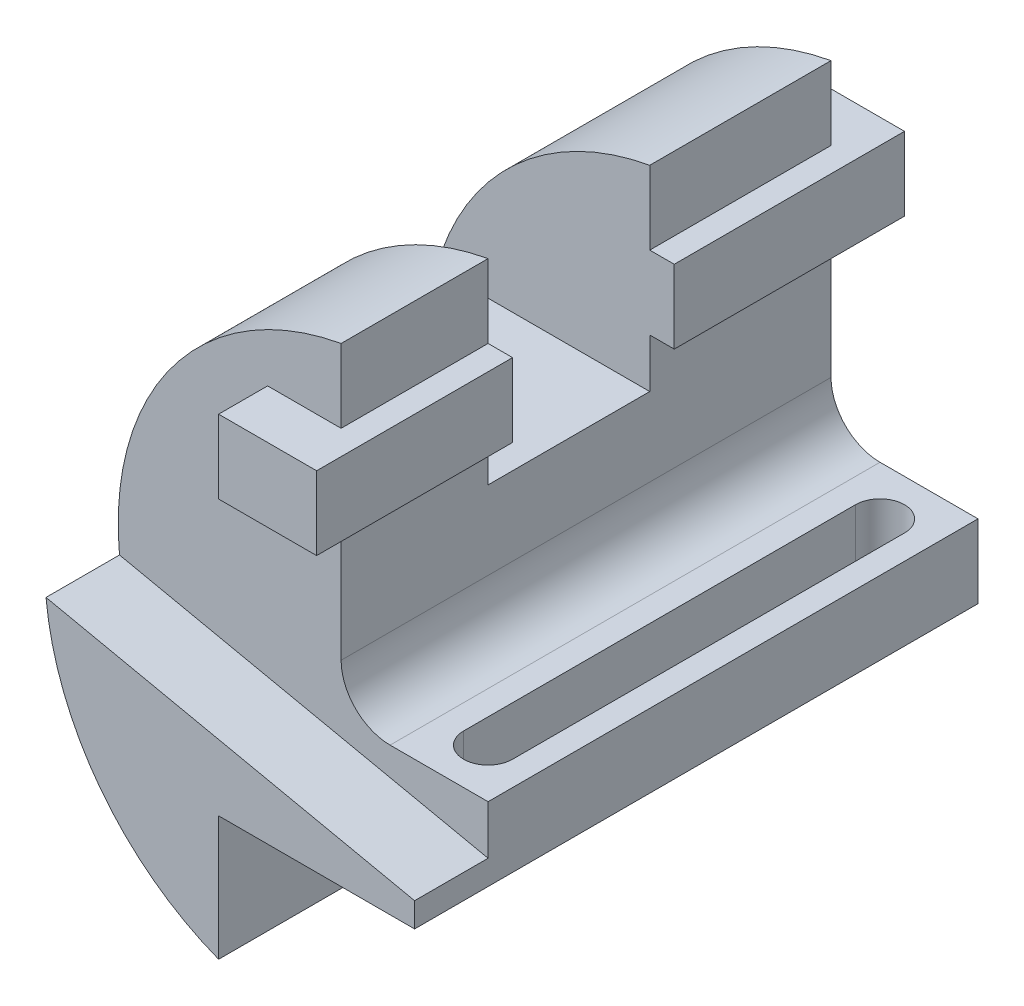
SolidWorks part; units mm, degrees
material "1060 Alloy"
ref_plane "Front Plane" through (0, 0, 0) normal (0, 0, 1) x (1, 0, 0)
ref_plane "Top Plane" through (0, 0, 0) normal (0, 1, 0) x (1, 0, 0)
ref_plane "Right Plane" through (0, 0, 0) normal (1, 0, 0) x (0, 0, -1)
sketch "Sketch1" plane through (0, 0, 0) normal (0, 0, 1) x (1, 0, 0)
  line L0 (0, 0) -> (0, 15)
  line L1 (0, 15) -> (-30, 15)
  line L2 (-30, 15) -> (-30, 81)
  line L3 (0, 0) -> (-40, 0)
  line L4 (-40, 0) -> (-40, -25.3628)
  arc A0 (-30, 81) -> (-40, -25.3628) centre (-20, 26.4083) ccw
  dimension "D5" = 55.5
  dimension "D1" = 15
  dimension "D2" = 20
  dimension "D3" = 40
  dimension "D4" = 10
  dimension "D6" = 66
extrude "Boss-Extrude2" add sketch "Sketch1" along normal blind 115
sketch "Sketch2" plane through (0, 0, 115) normal (0, 0, 1) x (1, 0, 0)
  line L0 (0, 5) -> (-75.235, 20.9917)
  line L1 (0, 0) -> (0, 15) construction
  line L8 (-40, 0) -> (0, 0)
  line L9 (0, 0) -> (0, 15)
  line L10 (0, 15) -> (-30, 15)
  line L11 (-30, 15) -> (-30, 81)
  line L12 (-40, -25.3628) -> (-40, 0)
  line L14 (0, 5) -> (0, 15)
  line L15 (0, 15) -> (-30, 15)
  line L16 (-30, 15) -> (-30, 81)
  arc A0 (-30, 81) -> (-40, -25.3628) centre (-20, 26.4083) ccw construction
  arc A2 (-30, 81) -> (-40, -25.3628) centre (-20, 26.4083) ccw
  arc A3 (-30, 81) -> (-75.235, 20.9917) centre (-20, 26.4083) ccw
  point P7 (0, 0)
  point P8 (0, 0)
  point P12 (0, 0)
  point P13 (0, 0)
  point P14 (0, 0)
  dimension "D1" = 5
  dimension "D2" = 78
  dimension "D3" = 0
extrude "Cut-Extrude1" cut sketch "Sketch2" against normal blind 15
sketch "Sketch4" plane through (0, 0, 0) normal (0, 0, -1) x (-1, 0, 0)
  line L0 (30, 15) -> (30, 81) construction
  line L1 (25, 66) -> (45, 66)
  line L2 (25, 66) -> (25, 51)
  line L3 (25, 51) -> (45, 51)
  line L4 (45, 66) -> (45, 51)
  dimension "D1" = 15
  dimension "D2" = 20
  dimension "D3" = 5
  dimension "D4" = 15
extrude "Boss-Extrude4" add sketch "Sketch4" against normal offset from surface 5 and the other way blind 10 up to face at (-32.3604, -0.8725, 115)
sketch "Sketch5" plane through (-30, 0, 0) normal (1, 0, 0) x (0, 0, -1)
  line L0 (-100, 81) -> (0, 81) construction
  line L1 (-70, 81) -> (-37, 81)
  line L2 (-70, 81) -> (-70, 41)
  line L3 (-70, 41) -> (-37, 41)
  line L4 (-37, 81) -> (-37, 41)
  line L5 (-100, 66) -> (-100, 81) construction
  line L6 (-100, 51) -> (0, 51) construction
  dimension "D1" = 30
  dimension "D2" = 33
  dimension "D3" = 10
extrude "Cut-Extrude3" cut sketch "Sketch5" against normal through all both and the other way through all
sketch "Sketch6" plane through (0, 15, 0) normal (0, 1, 0) x (1, 0, 0)
  line L0 (-10, -10) -> (-10, -90) construction
  line L1 (-5, -10) -> (-5, -90)
  line L2 (-15, -10) -> (-15, -90)
  line L3 (0, -100) -> (0, 0) construction
  line L4 (0, 0) -> (-30, 0) construction
  arc A0 (-5, -10) -> (-15, -10) centre (-10, -10) ccw
  arc A1 (-15, -90) -> (-5, -90) centre (-10, -90) ccw
  point P2 (-10, -50)
  dimension "D2" = 10
  dimension "D1" = 80
  dimension "D3" = 10
  dimension "D4" = 10
extrude "Cut-Extrude4" cut sketch "Sketch6" against normal through all both
fillet "Fillet1" radius 10 1 edges at (-30, 15, 50)
